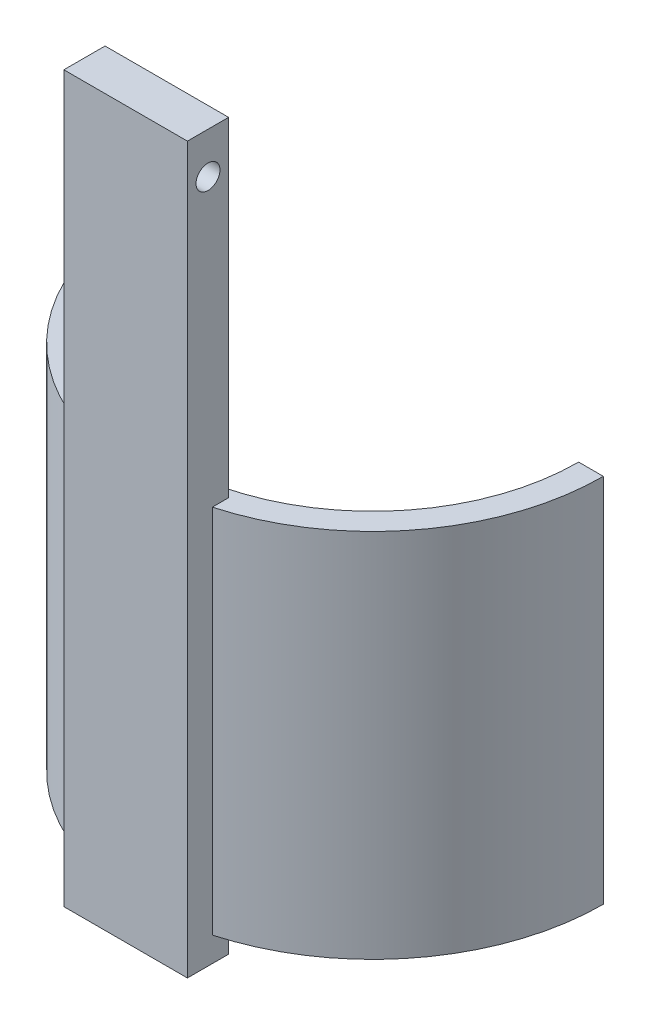
SolidWorks part; units mm, degrees
ref_plane "前视基准面" through (0, 0, 0) normal (0, 0, 1) x (1, 0, 0)
ref_plane "上视基准面" through (0, 0, 0) normal (0, 1, 0) x (1, 0, 0)
ref_plane "右视基准面" through (0, 0, 0) normal (1, 0, 0) x (0, 0, -1)
sketch "草图1" plane through (0, 0, 0) normal (0, 0, 1) x (1, 0, 0)
  line L0 (0.4458, 0) -> (4.8673, -2.8236)
  line L1 (0.4458, 0) -> (0.4458, 45)
  line L2 (0.4458, 45) -> (-2.5542, 45)
  line L3 (-2.5542, 45) -> (-2.5542, 0)
  line L4 (-2.5542, 0) -> (1.8673, -2.8236)
  line L5 (1.8673, -2.8236) -> (4.8673, -2.8236)
  line L8 (0.4458, 0) -> (25.4458, 0) construction
  line L9 (25.4458, 0) -> (25.4458, 34.0606) construction
  dimension "D1" = 45
  dimension "D2" = 3
  dimension "D3" = 3
  dimension "D4" = 45
  dimension "D5" = 25
revolve "旋转1" add sketch "草图1" angle 180 about L9
sketch "草图2" plane through (0, 45, 0) normal (0, 1, 0) x (1, 0, 0)
  line L0 (25.4458, -25) -> (32.9458, -25)
  line L1 (25.4458, -25) -> (17.9458, -25)
  line L3 (32.9458, -25) -> (17.9458, -25)
  line L4 (32.9458, -25) -> (32.9458, -30)
  line L5 (32.9458, -30) -> (17.9458, -30)
  line L6 (17.9458, -25) -> (17.9458, -30)
  line L7 (32.9458, -25) -> (17.9458, -25)
  line L8 (32.9458, -25) -> (32.9458, -30)
  line L9 (32.9458, -30) -> (17.9458, -30)
  line L10 (17.9458, -25) -> (17.9458, -30)
  arc A0 (0.4458, 0) -> (50.4458, 0) centre (25.4458, 0) ccw construction
  arc M4 (-2.5542, 0) -> (53.4458, 0) centre (25.4458, 0) ccw
  dimension "D1" = 7.5
  dimension "D2" = 7.5
  dimension "D3" = 5
extrude "凸台-拉伸2" add sketch "草图2" along normal blind 40 and the other way blind 48 contours L6 L5 L4 M4 | L1 L6 L4 L0 M4
sketch "草图3" plane through (32.9458, 0, 0) normal (1, 0, 0) x (0, 0, -1)
  line L0 (-30, 80) -> (-25, 80) construction
  line L1 (-30, -3) -> (-30, 85) construction
  line L2 (-25, 45) -> (-25, 85) construction
  line L3 (-27.5, 85) -> (-27.5, 75.6218) construction
  line L4 (-25, 85) -> (-30, 85) construction
  circle A0 centre (-27.5, 80) radius 1.45
  point P11 (-27.5, 80)
  dimension "D1" = 5
extrude "切除-拉伸1" cut sketch "草图3" against normal blind 40
